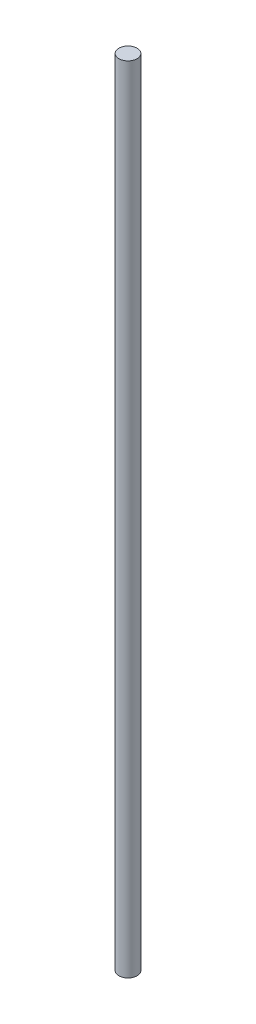
SolidWorks part; units mm, degrees
ref_plane "Front Plane" through (0, 0, 0) normal (0, 0, 1) x (1, 0, 0)
ref_plane "Top Plane" through (0, 0, 0) normal (0, 1, 0) x (1, 0, 0)
ref_plane "Right Plane" through (0, 0, 0) normal (1, 0, 0) x (0, 0, -1)
sketch "Sketch1" plane through (0, 0, 0) normal (0, 1, 0) x (1, 0, 0)
  circle A0 centre (0, 0) radius 6
  dimension "D1" = 12
extrude "Boss-Extrude1" add sketch "Sketch1" along normal blind 523
equation "\"d\"= 12"
equation "\"l\"= 523"
equation "\"D1@Boss-Extrude1\"= \"l\""
equation "\"D1@Sketch1\"=\"d\""
